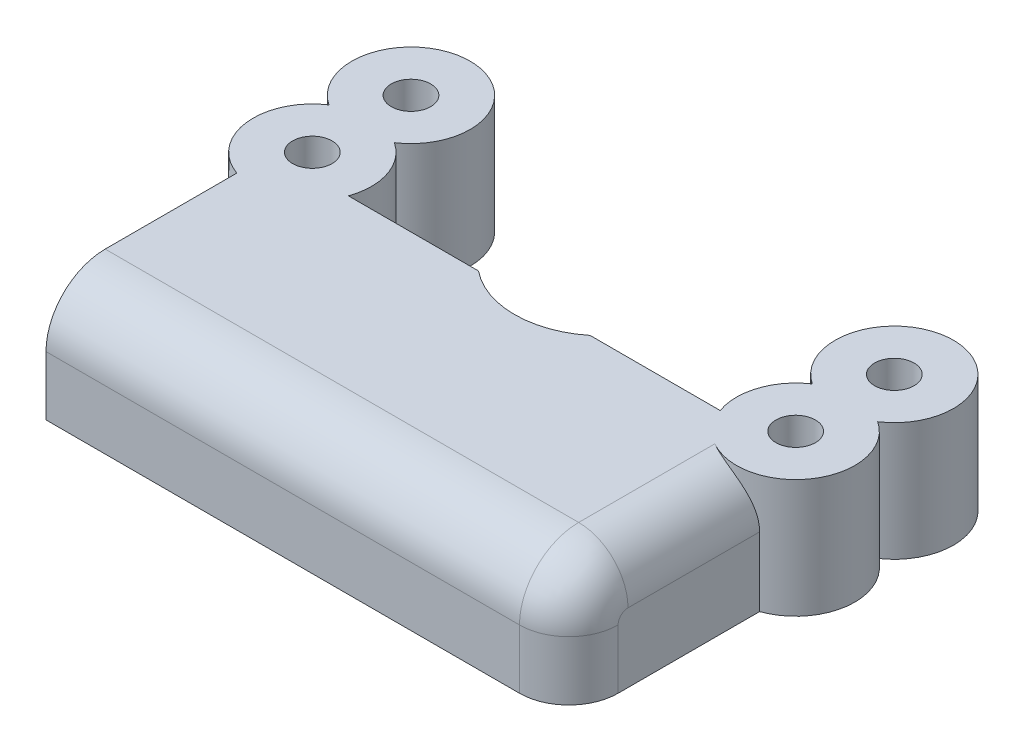
SolidWorks part; units mm, degrees
ref_plane "Front Plane" through (0, 0, 0) normal (0, 0, 1) x (1, 0, 0)
ref_plane "Top Plane" through (0, 0, 0) normal (0, 1, 0) x (1, 0, 0)
ref_plane "Right Plane" through (0, 0, 0) normal (1, 0, 0) x (0, 0, -1)
sketch "Sketch1" plane through (0, 0, 0) normal (0, 1, 0) x (1, 0, 0)
  line L0 (-34.8608, 12.4858) -> (-34.8608, -12.5142)
  line L1 (-34.8608, 12.4858) -> (18.1392, 12.4858)
  line L2 (-34.8608, -12.5142) -> (18.1392, -12.5142)
  line L3 (18.1392, 12.4858) -> (18.1392, -12.5142)
  line L4 (-34.8608, -12.5142) -> (18.1392, -12.5142)
  line L5 (-34.8608, -12.5142) -> (-34.8608, -7.5458)
  line L6 (18.1392, -12.5142) -> (18.1392, -7.5458)
  line L7 (-34.8608, -7.5458) -> (18.1392, -7.5458)
  line L9 (14.1392, 20.5175) -> (18.1392, 20.5175)
  line L10 (14.1392, 20.5175) -> (14.1392, -7.5458)
  line L11 (14.1392, -7.5458) -> (18.1392, -7.5458)
  line L12 (18.1392, 20.5175) -> (18.1392, -7.5458)
  line L13 (14.1392, 20.5175) -> (18.1392, -7.5458) construction
  line L14 (14.1392, -7.5458) -> (18.1392, 20.5175) construction
  circle A0 centre (16.1392, 12.4858) radius 2
  circle A1 centre (-32.8608, 12.4858) radius 2
  circle A2 centre (-32.8608, 12.4858) radius 6
  circle A3 centre (16.1392, 12.4858) radius 6
  circle A4 centre (-32.8608, 22.4858) radius 2
  circle A5 centre (16.1392, 22.4858) radius 2
  circle A6 centre (-32.8608, 22.4858) radius 6
  circle A7 centre (16.1392, 22.4858) radius 6
  circle A8 centre (-8.3608, 18.0889) radius 10
  point P20 (16.1392, 6.4858)
  dimension "D1" = 2
  dimension "D2" = 49
  dimension "D3" = 0
  dimension "D4" = 4
  dimension "D5" = 25
  dimension "D7" = 4
  dimension "D8" = 4
  dimension "D9" = 10
  dimension "D10" = 10
  dimension "D11" = 12
  dimension "D12" = 12
  dimension "D13" = 12
  dimension "D14" = 12
  dimension "D15" = 20
  dimension "D16" = 24.5
  dimension "D6" = 2
extrude "Boss-Extrude1" add sketch "Sketch1" along normal blind 10 contours A2 A6 A4 | A3 A7 A5 | A2 A6 | A6 A2 L0 A1 L1 | L0 A2 L1 A1 | L1 A3 L3 A0 | L7 L0 L2 L3 | A3 L10 L7 L12 | A7 L12 L3 A3 | A7 A3 L1 L10 | A5 L9 L10 A3 L12 | A7 L10 A0 L12 | L12 A7 A3 | A3 A7 L10 | L1 A3 L10 | L10 A7 L12 A3
sketch "Sketch2" plane through (0, 10, 0) normal (0, 1, 0) x (1, 0, 0)
  line L1 (-34.8608, -12.5142) -> (18.1392, -12.5142)
  line L2 (-34.8608, -12.5142) -> (-34.8608, 10.4858)
  line L3 (-34.8608, 10.4858) -> (18.1392, 10.4858)
  line L4 (18.1392, -12.5142) -> (18.1392, 10.4858)
extrude "Boss-Extrude2" add sketch "Sketch2" along normal blind 2
fillet "Fillet1" radius 6 1 edges at (-8.3608, 12, 12.5142)
sketch "Sketch5" plane through (0, 10, 0) normal (0, 1, 0) x (1, 0, 0)
  circle A0 centre (16.1392, 22.4858) radius 6
  circle A1 centre (16.1392, 22.4858) radius 2
  circle A2 centre (16.1392, 12.4858) radius 2
  circle A3 centre (16.1392, 12.4858) radius 6
  circle A4 centre (-32.8608, 22.4858) radius 6
  circle A5 centre (-32.8608, 22.4858) radius 2
  circle A6 centre (-32.8608, 12.4858) radius 2
  circle A7 centre (-32.8608, 12.4858) radius 6
  circle M1 centre (16.1392, 22.4858) radius 2
  circle M2 centre (16.1392, 12.4858) radius 2
  arc M4 (18.1392, 6.829) -> (19.4558, 17.4858) centre (16.1392, 12.4858) ccw
  arc M5 (19.4558, 17.4858) -> (12.8226, 17.4858) centre (16.1392, 22.4858) ccw
  arc M6 (12.8226, 17.4858) -> (10.4823, 10.4858) centre (16.1392, 12.4858) ccw
  line M8 (16.1392, 10.4858) -> (18.1392, 10.4858)
  line M9 (10.4823, 10.4858) -> (16.1392, 10.4858)
  line M10 (18.1392, 10.4858) -> (18.1392, 6.829)
extrude "Boss-Extrude5" add sketch "Sketch5" along normal blind 2 contours A7 A4 A5 | A4 A7 | A4 A7 A6 | A3 M5 M1 | A0 A3 | A0 M6 M9 M2 M8 M10 M4 | A3 M9 M10 M8
sketch "Sketch7" plane through (0, 12, 0) normal (0, 1, 0) x (1, 0, 0)
  circle A0 centre (-8.3608, 17.4858) radius 9
  circle A1 centre (16.1392, 22.4858) radius 2 construction
  circle A2 centre (16.1392, 12.4858) radius 2 construction
  dimension "D1" = 18
  dimension "D2" = 24.5
  dimension "D3" = 5
extrude "Cut-Extrude1" cut sketch "Sketch7" against normal blind 2
fillet "Fillet2" radius 5 3 edges at (18.1392, 3, 12.5142) (18.1392, 10.2426, 10.7568) (18.1392, 12, -0.1574)
